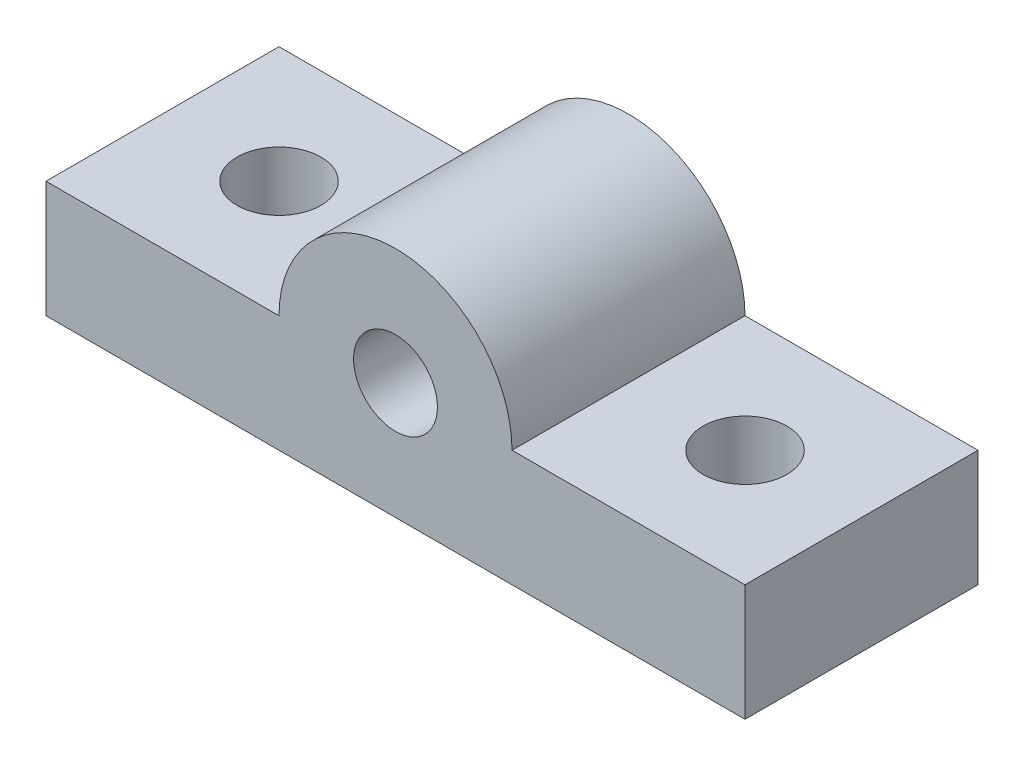
SolidWorks part; units mm, degrees
ref_plane "Front Plane" through (0, 0, 0) normal (0, 0, 1) x (1, 0, 0)
ref_plane "Top Plane" through (0, 0, 0) normal (0, 1, 0) x (1, 0, 0)
ref_plane "Right Plane" through (0, 0, 0) normal (1, 0, 0) x (0, 0, -1)
sketch "Sketch1" plane through (0, 0, 0) normal (0, 1, 0) x (1, 0, 0)
  line L0 (-12.7, 0) -> (12.7, 0) construction
  line L1 (-19.05, 6.35) -> (19.05, 6.35)
  line L2 (-19.05, 6.35) -> (-19.05, -6.35)
  line L3 (-19.05, -6.35) -> (19.05, -6.35)
  line L4 (19.05, 6.35) -> (19.05, -6.35)
  line L5 (-19.05, 6.35) -> (19.05, -6.35) construction
  line L6 (-19.05, -6.35) -> (19.05, 6.35) construction
  circle A0 centre (-12.7, 0) radius 2.286
  circle A1 centre (12.7, 0) radius 2.286
  point P0 (0, 0)
  point P6 (12.3042, 0)
  point P10 (-13.0694, 0)
  point P13 (0, 0)
  dimension "D4" = 4.572
  dimension "D1" = 38.1
  dimension "D2" = 12.7
  dimension "D3" = 25.4
extrude "Boss-Extrude1" add sketch "Sketch1" along normal blind 6.35
sketch "Sketch4" plane through (0, 0, 6.35) normal (0, 0, 1) x (1, 0, 0)
  line L0 (-19.05, 6.35) -> (19.05, 6.35) construction
  line L1 (-19.05, 0) -> (19.05, 0) construction
  circle A0 centre (0, 6.35) radius 6.35
extrude "Boss-Extrude2" add sketch "Sketch4" against normal up to surface (12.7 mm away) up to face at (0, 3.175, -6.35)
sketch "Sketch2" plane through (0, 0, 6.35) normal (0, 0, 1) x (1, 0, 0)
  circle A0 centre (0, 6.35) radius 2.286
  circle A1 centre (0, 6.35) radius 2.286 construction
  point P2 (0, 6.35)
  point P4 (-11.1125, 6.35)
extrude "Cut-Extrude1" cut sketch "Sketch2" against normal through all
